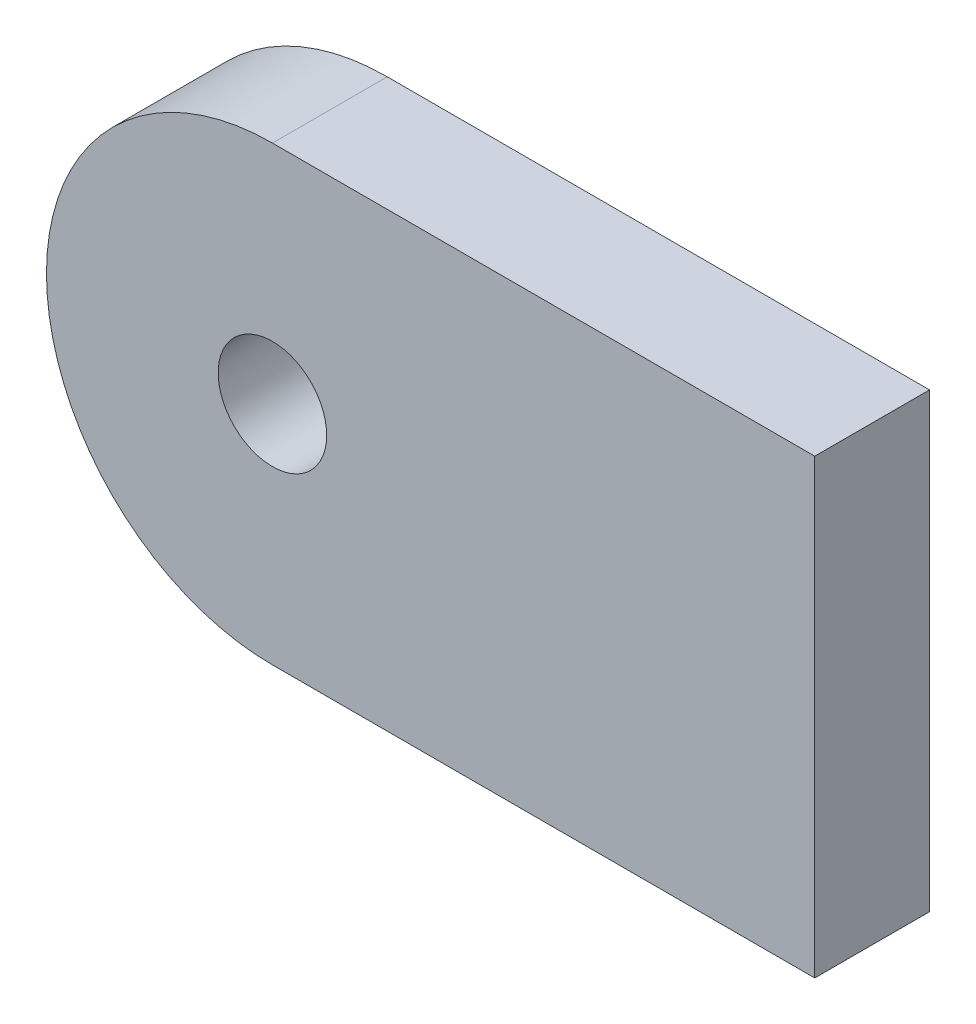
SolidWorks part; units mm, degrees
ref_plane "Front Plane" through (0, 0, 0) normal (0, 0, 1) x (1, 0, 0)
ref_plane "Top Plane" through (0, 0, 0) normal (0, 1, 0) x (1, 0, 0)
ref_plane "Right Plane" through (0, 0, 0) normal (1, 0, 0) x (0, 0, -1)
sketch "Sketch1" plane through (0, 0, 36.0153) normal (0, 0, 1) x (1, 0, 0)
  line L1 (-1.6088, 1.4212) -> (-31.6088, 1.4212)
  line L2 (-1.6088, 1.4212) -> (-1.6088, 26.4212)
  line L3 (-1.6088, 26.4212) -> (-31.6088, 26.4212)
  arc A0 (-31.6088, 1.4212) -> (-31.6088, 26.4212) centre (-31.6088, 13.9212) cw
  circle A1 centre (-31.6088, 13.9212) radius 3
  dimension "D1" = 25
  dimension "D2" = 30
extrude "Boss-Extrude1" add sketch "Sketch1" along normal blind 6.35
